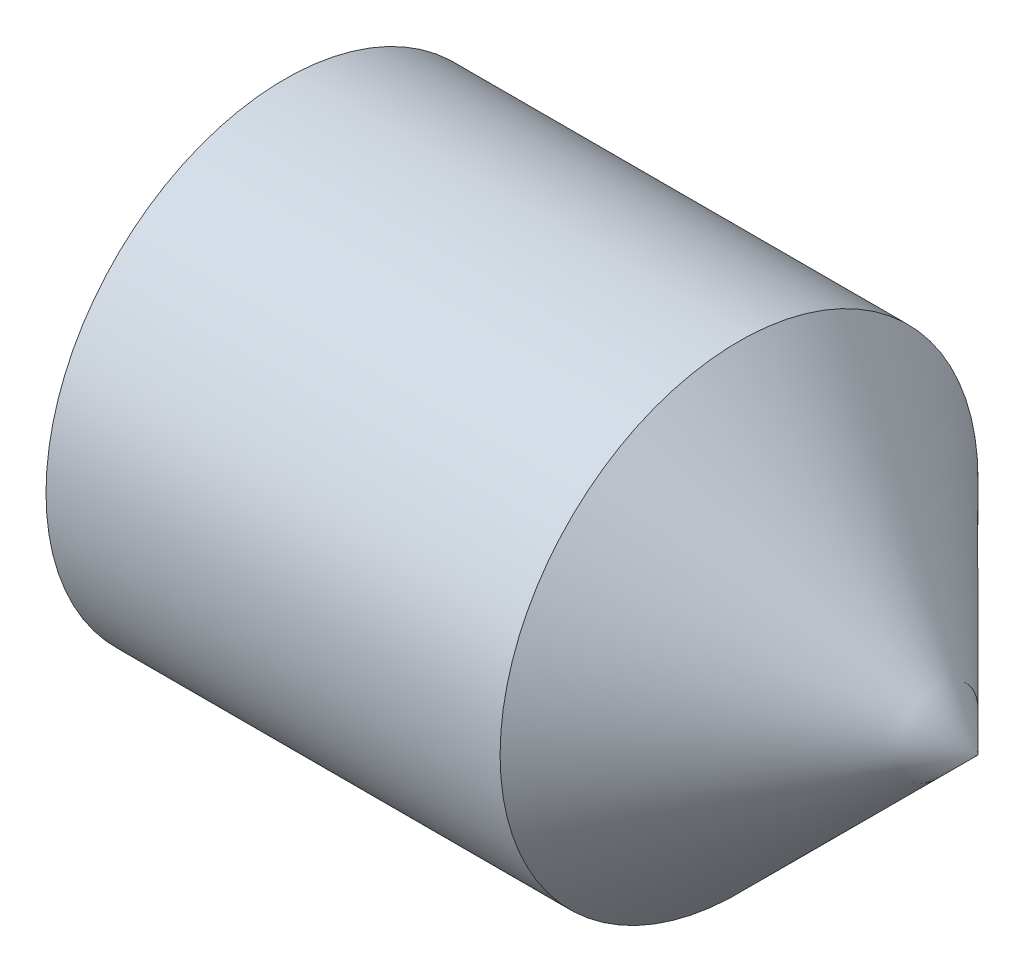
SolidWorks part; units mm, degrees
revolve "BaseBody" add sketch "BodySke" angle 360 about L5
sketch "BodySke" plane through (0, 0, 0) normal (0, 0, 1) x (1, 0, 0)
  line L0 (0, 0) -> (0, 3.3095)
  line L1 (0, 3.3095) -> (0.3987, 4)
  line L2 (0.3987, 4) -> (8, 4)
  line L3 (8, 4) -> (12, 0)
  line L4 (12, 0) -> (0, 0)
  line L5 (-12.7, 0) -> (88.9, 0) construction
  line L6 (8, -4) -> (12, 0) construction
  line L7 (0.625, 15.875) -> (0.625, -3.175) construction
  line L8 (0, -3.3095) -> (0.3987, -4) construction
  dimension "Diameter" = 8
  dimension "Drive_ch_ang" = 60
  dimension "Minor_dia" = 6.619
  dimension "Advance" = 1.25
  dimension "Cone_ang" = 90
  dimension "Length" = 12
cosmetic thread "ThreadCosmetic" [suppressed] parameters "Thread_minor"=6.619
ref_plane "Plane1" through (0, 0, 0) normal (0, 0, 1) x (1, 0, 0)
ref_plane "Plane2" through (0, 0, 0) normal (0, 1, 0) x (1, 0, 0)
ref_plane "Plane3" through (0, 0, 0) normal (1, 0, 0) x (0, 0, -1)
sketch "Sketch2" plane through (0, 0, 0) normal (-1, 0, 0) x (0, 0, 1)
  line L0 (1.1547, 2) -> (-1.1547, 2)
  line L1 (-1.1547, 2) -> (-2.3094, 0)
  line L2 (1.1547, 2) -> (2.3094, 0)
  line L3 (1.1547, -2) -> (2.3094, 0)
  line L4 (1.1547, -2) -> (-1.1547, -2)
  line L5 (-1.1547, -2) -> (-2.3094, 0)
  dimension "Hex_size" = 4
  dimension "D2" = 2
  dimension "D3" = 2
extrude "Hex" cut sketch "Sketch2" against normal blind 5
sketch "ThdSchSke" plane through (0, 0, 0) normal (0, 0, 1) x (1, 0, 0)
  line L0 (0.3987, -3.3095) -> (-0.0848, -4)
  line L1 (0.3987, -3.3095) -> (0.8822, -4)
  line L2 (0.8822, -4) -> (0.8822, -5)
  line L3 (-3.175, 0) -> (5.1513, 0) construction
  line L4 (0.3987, 4) -> (0.3987, -4) construction
  line L5 (0.8822, -5) -> (-0.0848, -5)
  line L6 (-0.0848, -5) -> (-0.0848, -4)
  dimension "Thread_minor" = 6.619
  dimension "Diameter" = 8
revolve "ThreadSchematic" [suppressed] cut sketch "ThdSchSke" angle 360 about L3
pattern_linear "ThdSchPat" [suppressed]
equation "\"D2@Sketch2\" = \"Hex_size@Sketch2\" / 2"
equation "\"D3@Sketch2\" = \"Hex_size@Sketch2\" / 2"
equation "\"Thread_minor@ThreadCosmetic\" = \"Minor_dia@BodySke\""
equation "\"Thread_minor@ThdSchSke\" = \"Thread_minor@ThreadCosmetic\""
equation "\"Diameter@ThdSchSke\" = \"Diameter@BodySke\""
equation "\"Overcut@ThdSchSke\" = \"Diameter@BodySke\" * 1.25"
equation "\"Num_threads@ThdSchPat\" = int( (\"Length@BodySke\" - ( ( ( \"Diameter@BodySke\" - \"Minor_dia@BodySke\" ) * 0.5 ) / tan( \"Drive_ch_ang@BodySke\" * 0.017453292 ) ) - ( ( \"Diameter@BodySke\" * 0.5 ) / tan( \"Cone_ang@BodySke\" * 0.008726646 ) ) ) / \"Advance@BodySke\" + 0.999 )  + 1"
equation "\"Advance@ThdSchPat\" = (\"Length@BodySke\" - ( ( ( \"Diameter@BodySke\" - \"Minor_dia@BodySke\" ) * 0.5 ) / tan( \"Drive_ch_ang@BodySke\" * 0.017453292 ) ) - ( ( \"Diameter@BodySke\" * 0.5 ) / tan( \"Cone_ang@BodySke\" * 0.008726646 ) ) ) /  (\"Num_threads@ThdSchPat\" - 1) 'relax it"
equation "' \"Num_threads@ThdSchPat\" = \"Num_threads@ThdSchPat\" - sgn( \"Num_threads@ThdSchPat\" - 1) '---chamfered tips only---"
